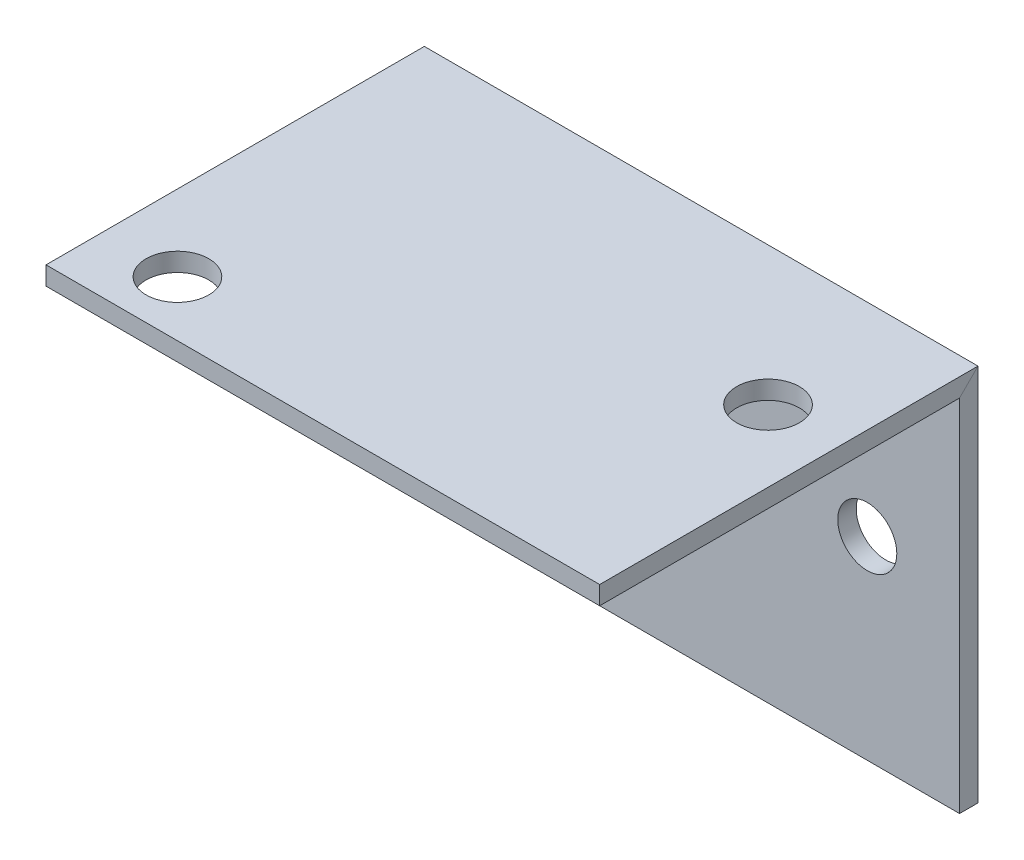
SolidWorks part; units mm, degrees
ref_plane "Plan de face" through (0, 0, 0) normal (0, 0, 1) x (1, 0, 0)
ref_plane "Plan de dessus" through (0, 0, 0) normal (0, 1, 0) x (1, 0, 0)
ref_plane "Plan de droite" through (0, 0, 0) normal (1, 0, 0) x (0, 0, -1)
sketch "Esquisse1" plane through (0, 0, 0) normal (0, 0, 1) x (1, 0, 0)
  line L1 (-15, 0.5) -> (15, 0.5)
  line L2 (-15, 0.5) -> (-15, -0.5)
  line L3 (-15, -0.5) -> (15, -0.5)
  line L4 (15, 0.5) -> (15, -0.5)
  line L5 (-15, 0.5) -> (15, -0.5) construction
  line L6 (-15, -0.5) -> (15, 0.5) construction
  point P0 (0, 0)
  dimension "D1" = 30
  dimension "D2" = 1
sketch "Esquisse6" plane through (0, 0, 0) normal (1, 0, 0) x (0, 0, -1)
  line L0 (0, 0) -> (20, 0)
  line L1 (0, -0.5) -> (0, 0.5) construction
  line L2 (20, 0) -> (20, -20)
  dimension "D1" = 20
  dimension "D2" = 20
sweep "Balayage1" add profiles "Esquisse1" path "Esquisse6"
sketch "Esquisse7" plane through (0, -0.5, 0) normal (0, -1, 0) x (1, 0, 0)
  circle A0 centre (-10.8773, -3) radius 1.7 construction
  circle A1 centre (-10.8773, -3) radius 1.7
  circle A2 centre (11.1227, -13) radius 1.7 construction
  circle A3 centre (11.1227, -13) radius 1.7
extrude "Enlèv. mat.-Extru.1" cut sketch "Esquisse7" against normal through all
sketch "Esquisse8" plane through (0, 0, -19.5) normal (0, 0, 1) x (1, 0, 0)
  line L0 (0, -20.644) -> (0, 0) construction
  line L1 (0, 0) -> (0, -20) construction
  line L2 (8.1815, -9.5) -> (0, -9.5) construction
  line L3 (-15, -0.5) -> (15, -0.5) construction
  circle A0 centre (10, -9.5) radius 1.6
  circle A1 centre (-10, -9.5) radius 1.6
  point P10 (0, 0)
  point P11 (0, 0)
  point P13 (0, -9.5)
  point P14 (0, 0)
  point P17 (0, 0)
  point P18 (9.0074, -9.5)
  point P19 (-0.0671, -20.6435)
  point P20 (10, -9.5)
  dimension "D2" = 3.2
  dimension "D1" = 9
  dimension "D3" = 10
extrude "Enlèv. mat.-Extru.2" cut sketch "Esquisse8" against normal through all
